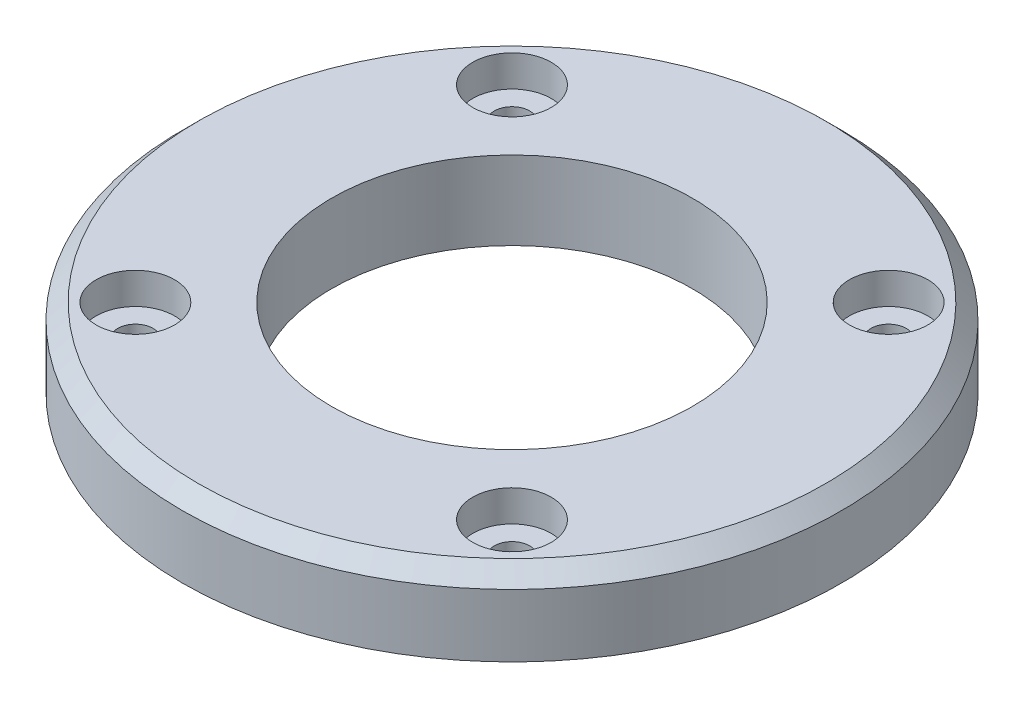
SolidWorks part; units mm, degrees
material "AISI 304"
ref_plane "前视基准面" through (0, 0, 0) normal (0, 0, 1) x (1, 0, 0)
ref_plane "上视基准面" through (0, 0, 0) normal (0, 1, 0) x (1, 0, 0)
ref_plane "右视基准面" through (0, 0, 0) normal (1, 0, 0) x (0, 0, -1)
sketch "Sketch1" plane through (0, 0, 0) normal (0, 1, 0) x (1, 0, 0)
  circle A0 centre (0, 0) radius 42
  circle A1 centre (0, 0) radius 23
  dimension "D1" = 84
  dimension "D2" = 46
extrude "Extrude1" add sketch "Sketch1" along normal blind 10
sketch "Sketch2" plane through (0, 10, 0) normal (0, 1, 0) x (1, 0, 0)
  line L1 (24, -24) -> (-24, -24) construction
  line L2 (24, -24) -> (24, 24) construction
  line L3 (24, 24) -> (-24, 24) construction
  line L4 (-24, -24) -> (-24, 24) construction
  line L5 (24, -24) -> (-24, 24) construction
  line L6 (24, 24) -> (-24, -24) construction
  point P0 (0, 0)
  dimension "D1" = 48
hole_wizard "CBORE for M4 Hex Head Bolt1" positions "3DSketch1" profile "Sketch3" counterbore size "M4" standard "GB"
sketch3d "3DSketch1"
  point P0 (-24, 10, -24)
  point P3 (24, 10, -24)
  point P6 (24, 10, 24)
  point P9 (-24, 10, 24)
sketch "Sketch3" plane through (-24, 10, -24) normal (1, 0, 0) x (0, 0, 1)
  line L0 (0, 0) -> (0, 21.1019)
  line L1 (0, 21.1019) -> (2.25, 19.75)
  line L2 (2.25, 19.75) -> (2.25, 4)
  line L3 (2.25, 4) -> (5, 4)
  line L4 (5, 4) -> (5, 0)
  line L5 (5, 0) -> (0, 0)
  line L10 (0, 21.1019) -> (-2.25, 19.75) construction
  line L11 (0, -6.35) -> (0, 107.95) construction
  dimension "孔直径" = 4.5
  dimension "孔深度" = 19.75
  dimension "柱形沉头孔直径" = 10
  dimension "柱形沉头孔深度" = 4
  dimension "导头角度" = 118
chamfer "Chamfer2" distance 2 angle 45 1 edges at (0, 10, 42)
